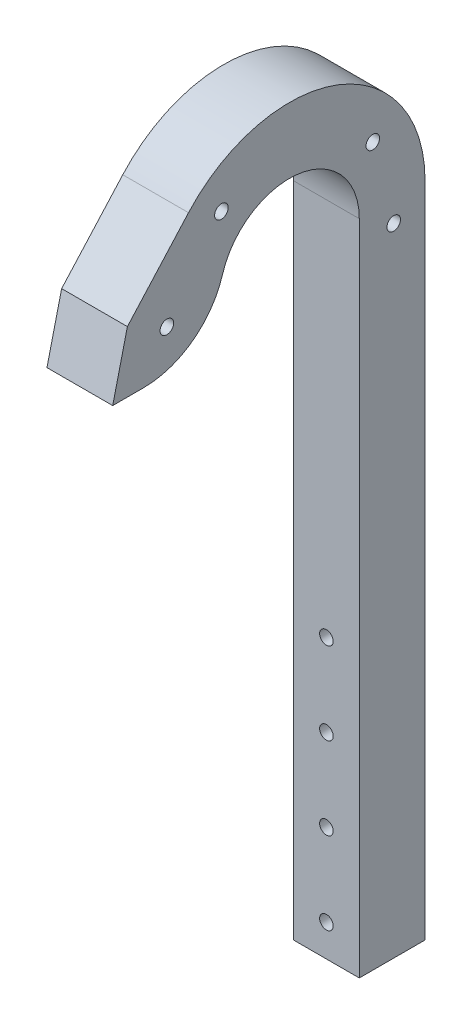
SolidWorks part; units mm, degrees
ref_plane "Front Plane" through (0, 0, 0) normal (0, 0, 1) x (1, 0, 0)
ref_plane "Top Plane" through (0, 0, 0) normal (0, 1, 0) x (1, 0, 0)
ref_plane "Right Plane" through (0, 0, 0) normal (1, 0, 0) x (0, 0, -1)
sketch "Sketch1" plane through (0, 0, 0) normal (1, 0, 0) x (0, 0, -1)
  line L1 (-96.1656, -175.7579) -> (-116.4856, -175.7579)
  line L2 (-96.1656, -175.7579) -> (-96.1656, 27.4421)
  line L4 (-116.4856, -175.7579) -> (-116.4856, 27.4421)
  line L6 (-169.2618, 55.4397) -> (-188.147, 34.4038)
  line L13 (-192.6856, 15.5289) -> (-183.0886, 15.5289)
  line L14 (-192.6856, 15.5289) -> (-188.147, 34.4038)
  arc A7 (-96.1656, 27.4421) -> (-169.2618, 55.4397) centre (-138.0756, 27.4421) ccw
  arc A10 (-116.4856, 27.4421) -> (-158.7572, 33.6387) centre (-138.0756, 27.4421) ccw
  circle A11 centre (-154.5856, 12.3984) radius 38.1 construction
  arc A13 (-183.0886, 15.5289) -> (-158.7572, 33.6387) centre (-183.0886, 40.9289) ccw
  point P0 (0, 0)
  point P14 (-58.53, 34.4038)
  point P19 (-96.7637, 29.8084)
  dimension "D2" = 43.18
  dimension "D3" = 25.4
  dimension "D5" = 203.2
  dimension "D1" = 20.32
  dimension "D4" = 76.2
extrude "Boss-Extrude1" add sketch "Sketch1" along normal blind 20.32
hole_wizard "#8 (0.199) Diameter Hole1" positions "Sketch2" profile "Sketch3" hole size "#8" standard "ANSI Inch" end condition through all
sketch "Sketch2" plane through (0, 0, 116.4856) normal (0, 0, 1) x (1, 0, 0)
  point P0 (10.16, -89.6972)
  point P3 (10.16, -115.0972)
  point P6 (10.16, -140.4972)
  point P9 (10.16, -165.8972)
  point P12 (10.16, -191.2972)
sketch "Sketch3" plane through (10.16, -89.6972, 116.4856) normal (1, 0, 0) x (0, -1, 0)
  line L0 (0, 0) -> (0, 20.32)
  line L1 (0, 20.32) -> (2.0955, 20.32)
  line L2 (2.0955, 20.32) -> (2.0955, 0)
  line L5 (2.0955, 0) -> (0, 0)
  line L11 (0, -6.35) -> (0, 107.95) construction
  dimension "Thru Hole Dia." = 4.191
  dimension "Thru Hole Depth" = 20.32
sketch "Sketch4" plane through (20.32, 0, 0) normal (1, 0, 0) x (0, 0, -1)
  circle A0 centre (-175.9493, 28.2266) radius 2.0955
  circle A1 centre (-159.0992, 50.6839) radius 2.0955
  circle A2 centre (-112.312, 45.8717) radius 2.0955
  circle A3 centre (-105.8514, 20.8651) radius 2.0955
extrude "Cut-Extrude1" cut sketch "Sketch4" against normal through all both and the other way through all
